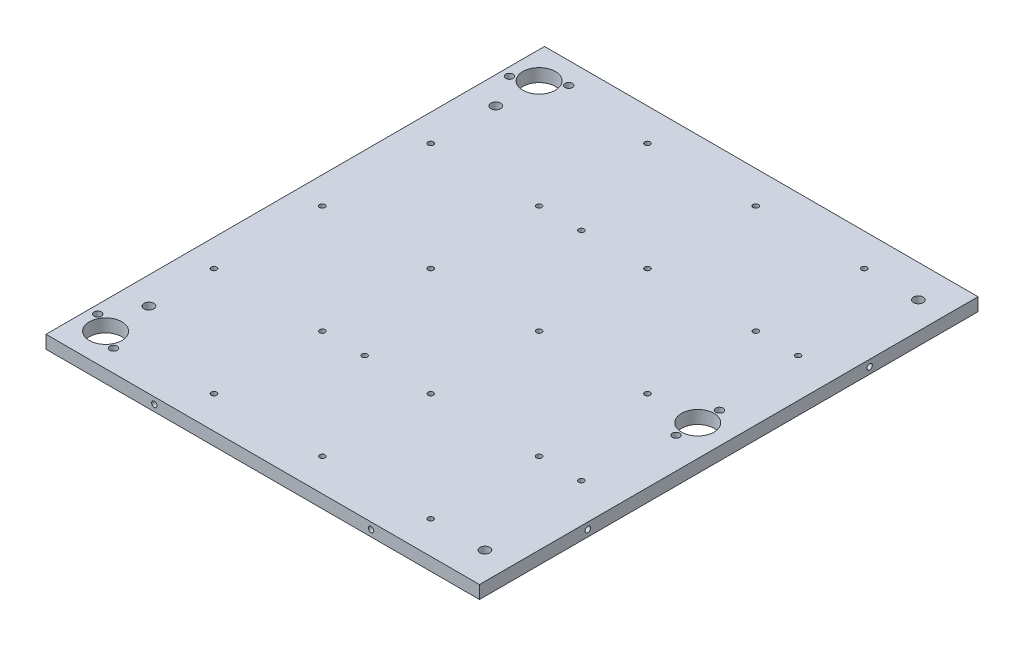
SolidWorks part; units mm, degrees
ref_plane "Ebene vorne" through (0, 0, 0) normal (0, 0, 1) x (1, 0, 0)
ref_plane "Ebene oben" through (0, 0, 0) normal (0, 1, 0) x (1, 0, 0)
ref_plane "Ebene rechts" through (0, 0, 0) normal (1, 0, 0) x (0, 0, -1)
ref_plane "Ebene1" through (0, -162, 0) normal (0, -1, 0) x (1, 0, 0)
sketch "Skizze1" plane through (0, -162, 0) normal (0, -1, 0) x (1, 0, 0)
  line L0 (-2.383, 209.2265) -> (-2.383, -20.7735)
  line L1 (-2.383, -20.7735) -> (197.617, -20.7735)
  line L2 (197.617, -20.7735) -> (197.617, 209.2265)
  line L3 (197.617, 209.2265) -> (-2.383, 209.2265)
extrude "Aufsatz-Linear austragen1" add sketch "Skizze1" against normal blind 6
hole_wizard "Pillar Mounting A" positions "Skizze3" profile "Skizze2" hole size "Ø3.4" standard "Ansi Metrisch"
sketch "Skizze3" plane through (0, -162, 0) normal (0, -1, 0) x (-1, 0, 0)
  point P0 (-1.4567, 0.7735)
  point P1 (-18.7772, 10.7735)
sketch "Skizze2" plane through (1.4567, -162, -0.7735) normal (1, 0, 0) x (0, 0, -1)
  line L0 (0, 0) -> (0, 6)
  line L1 (0, 6) -> (1.7, 6)
  line L2 (1.7, 6) -> (1.7, 0)
  line L5 (1.7, 0) -> (0, 0)
  line L11 (0, -6.35) -> (0, 107.95) construction
  dimension "Bohrerdurchmesser" = 3.4
  dimension "Bohrungstiefe" = 6
hole_wizard "Pillar Grommet" positions "Skizze5" profile "Skizze4" hole size "Ø15.0" standard "Ansi Metrisch"
sketch "Skizze5" plane through (0, -162, 0) normal (0, -1, 0) x (-1, 0, 0)
  point P0 (-10.117, 5.7735)
  point P1 (-10.117, -194.2265)
  point P2 (-183.3221, -94.2265)
sketch "Skizze4" plane through (10.117, -162, -5.7735) normal (1, 0, 0) x (0, 0, -1)
  line L0 (0, 0) -> (0, 6)
  line L1 (0, 6) -> (7.5, 6)
  line L2 (7.5, 6) -> (7.5, 0)
  line L5 (7.5, 0) -> (0, 0)
  line L11 (0, -6.35) -> (0, 107.95) construction
  dimension "Bohrerdurchmesser" = 15
  dimension "Bohrungstiefe" = 6
hole_wizard "Pillar Mounting B" positions "Skizze7" profile "Skizze6" hole size "Ø3.4" standard "Ansi Metrisch"
sketch "Skizze7" plane through (0, -156, 0) normal (0, 1, 0) x (1, 0, 0)
  point P0 (183.3221, -84.2265)
  point P1 (18.7772, -199.2265)
  point P2 (1.4567, -189.2265)
  point P3 (183.3221, -104.2265)
sketch "Skizze6" plane through (183.3221, -156, 84.2265) normal (1, 0, 0) x (0, 0, 1)
  line L0 (0, 0) -> (0, 6)
  line L1 (0, 6) -> (1.7, 6)
  line L2 (1.7, 6) -> (1.7, 0)
  line L5 (1.7, 0) -> (0, 0)
  line L11 (0, -6.35) -> (0, 107.95) construction
  dimension "Bohrerdurchmesser" = 3.4
  dimension "Bohrungstiefe" = 6
hole_wizard "M3 Mounting Grid" positions "Skizze9" profile "Skizze8" tap size "M3x0.5" standard "Ansi Metrisch" end condition through all
sketch "Skizze9" plane through (0, -162, 0) normal (0, -1, 0) x (-1, 0, 0)
  point P0 (-60.117, -94.2265)
  point P1 (-60.117, 5.7735)
  point P2 (-60.117, -44.2265)
  point P3 (-110.117, -44.2265)
  point P4 (-110.117, -194.2265)
  point P5 (-110.117, -94.2265)
  point P6 (-110.117, 5.7735)
  point P7 (-110.117, -144.2265)
  point P8 (-60.117, -144.2265)
  point P9 (-10.117, -144.2265)
  point P10 (-10.117, -44.2265)
  point P11 (-60.117, -194.2265)
  point P12 (-160.117, -94.2265)
  point P13 (-160.117, -44.2265)
  point P14 (-160.117, -194.2265)
  point P15 (-160.117, 5.7735)
  point P16 (-160.117, -144.2265)
  point P17 (-10.117, -94.2265)
sketch "Skizze8" plane through (60.117, -162, 94.2265) normal (1, 0, 0) x (0, 0, -1)
  line L0 (0, 0) -> (0, 6)
  line L1 (0, 6) -> (1.25, 6)
  line L2 (1.25, 6) -> (1.25, 0)
  line L5 (1.25, 0) -> (0, 0)
  line L11 (0, -6.35) -> (0, 107.95) construction
  dimension "Bohrerdurchmesser" = 2.5
  dimension "Bohrungstiefe" = 6
cosmetic thread "Bohrungsgewinde9" parameters "D2"=3
cosmetic thread "Bohrungsgewinde10" parameters "D2"=3
cosmetic thread "Bohrungsgewinde11" parameters "D2"=3
cosmetic thread "Bohrungsgewinde12" parameters "D2"=3
cosmetic thread "Bohrungsgewinde13" parameters "D2"=3
cosmetic thread "Bohrungsgewinde14" parameters "D2"=3
cosmetic thread "Bohrungsgewinde15" parameters "D2"=3
cosmetic thread "Bohrungsgewinde16" parameters "D2"=3
cosmetic thread "Bohrungsgewinde17" parameters "D2"=3
cosmetic thread "Bohrungsgewinde18" parameters "D2"=3
cosmetic thread "Bohrungsgewinde19" parameters "D2"=3
cosmetic thread "Bohrungsgewinde20" parameters "D2"=3
cosmetic thread "Bohrungsgewinde21" parameters "D2"=3
cosmetic thread "Bohrungsgewinde22" parameters "D2"=3
cosmetic thread "Bohrungsgewinde23" parameters "D2"=3
cosmetic thread "Bohrungsgewinde24" parameters "D2"=3
cosmetic thread "Bohrungsgewinde25" parameters "D2"=3
cosmetic thread "Bohrungsgewinde26" parameters "D2"=3
hole_wizard "Pedestal Mounting Hole" positions "Skizze11" profile "Skizze10" countersink size "M4" standard "Ansi Metrisch" end condition through all
sketch "Skizze11" plane through (0, -162, 0) normal (0, -1, 0) x (-1, 0, 0)
  point P0 (-10.117, -174.2265)
  point P1 (-185.117, -194.2265)
  point P2 (-185.117, 5.7735)
  point P3 (-10.117, -14.2265)
sketch "Skizze10" plane through (10.117, -162, 174.2265) normal (1, 0, 0) x (0, 0, -1)
  line L0 (0, 0) -> (0, 6)
  line L1 (0, 6) -> (2.25, 6)
  line L2 (2.25, 6) -> (2.25, 2.23)
  line L3 (2.25, 2.23) -> (4.48, 0)
  line L5 (4.48, 0) -> (0, 0)
  line L6 (-2.25, 2.23) -> (-4.48, 0) construction
  line L11 (0, -6.35) -> (0, 107.95) construction
  dimension "Bohrerdurchmesser" = 4.5
  dimension "Bohrungstiefe" = 6
  dimension "Senkdurchmesser (Oben)" = 8.96
  dimension "Senkwinkel (Oben)" = 90
hole_wizard "Side Cover Mounting Thread A" positions "Skizze13" profile "Skizze12" tap size "M3x0.5" standard "Ansi Metrisch"
sketch "Skizze13" plane through (0, 0, 209.2265) normal (0, 0, 1) x (1, 0, 0)
  point P0 (47.617, -159)
  point P1 (147.617, -159)
sketch "Skizze12" plane through (47.617, -159, 209.2265) normal (1, 0, 0) x (0, -1, 0)
  line L0 (0, 0) -> (0, 9.2511)
  line L1 (0, 9.2511) -> (1.25, 8.5)
  line L2 (1.25, 8.5) -> (1.25, 0)
  line L5 (1.25, 0) -> (0, 0)
  line L10 (0, 9.2511) -> (-1.25, 8.5) construction
  line L11 (0, -6.35) -> (0, 107.95) construction
  dimension "Bohrerdurchmesser" = 2.5
  dimension "Bohrungstiefe" = 8.5
  dimension "Spitzenwinkel" = 118
cosmetic thread "Bohrungsgewinde3" parameters "D1"=6, "D2"=3
cosmetic thread "Bohrungsgewinde4" parameters "D1"=6, "D2"=3
hole_wizard "Side Cover Mounting Thread B" positions "Skizze15" profile "Skizze14" tap size "M3x0.5" standard "Ansi Metrisch"
sketch "Skizze15" plane through (197.617, 0, 0) normal (1, 0, 0) x (0, 0, -1)
  point P0 (-29.2265, -159)
  point P1 (-159.2265, -159)
sketch "Skizze14" plane through (197.617, -159, 29.2265) normal (0, 1, 0) x (0, 0, -1)
  line L0 (0, 0) -> (0, 9.2511)
  line L1 (0, 9.2511) -> (1.25, 8.5)
  line L2 (1.25, 8.5) -> (1.25, 0)
  line L5 (1.25, 0) -> (0, 0)
  line L10 (0, 9.2511) -> (-1.25, 8.5) construction
  line L11 (0, -6.35) -> (0, 107.95) construction
  dimension "Bohrerdurchmesser" = 2.5
  dimension "Bohrungstiefe" = 8.5
  dimension "Spitzenwinkel" = 118
cosmetic thread "Bohrungsgewinde5" parameters "D1"=6, "D2"=3
cosmetic thread "Bohrungsgewinde6" parameters "D1"=6, "D2"=3
hole_wizard "Side Cover Mounting Thread  C" positions "Skizze17" profile "Skizze16" tap size "M3x0.5" standard "Ansi Metrisch"
sketch "Skizze17" plane through (0, 0, -20.7735) normal (0, 0, -1) x (-1, 0, 0)
  point P0 (-47.617, -159)
  point P1 (-147.617, -159)
sketch "Skizze16" plane through (47.617, -159, -20.7735) normal (1, 0, 0) x (0, 1, 0)
  line L0 (0, 0) -> (0, 9.2511)
  line L1 (0, 9.2511) -> (1.25, 8.5)
  line L2 (1.25, 8.5) -> (1.25, 0)
  line L5 (1.25, 0) -> (0, 0)
  line L10 (0, 9.2511) -> (-1.25, 8.5) construction
  line L11 (0, -6.35) -> (0, 107.95) construction
  dimension "Bohrerdurchmesser" = 2.5
  dimension "Bohrungstiefe" = 8.5
  dimension "Spitzenwinkel" = 118
cosmetic thread "Bohrungsgewinde1" parameters "D1"=6, "D2"=3
cosmetic thread "Bohrungsgewinde2" parameters "D1"=6, "D2"=3
hole_wizard "Side Cover Mounting Thread  D" positions "Skizze19" profile "Skizze18" tap size "M3x0.5" standard "Ansi Metrisch"
sketch "Skizze19" plane through (-2.383, 0, 0) normal (-1, 0, 0) x (0, 0, 1)
  point P0 (29.2265, -159)
  point P1 (159.2265, -159)
sketch "Skizze18" plane through (-2.383, -159, 29.2265) normal (0, 1, 0) x (0, 0, 1)
  line L0 (0, 0) -> (0, 9.2511)
  line L1 (0, 9.2511) -> (1.25, 8.5)
  line L2 (1.25, 8.5) -> (1.25, 0)
  line L5 (1.25, 0) -> (0, 0)
  line L10 (0, 9.2511) -> (-1.25, 8.5) construction
  line L11 (0, -6.35) -> (0, 107.95) construction
  dimension "Bohrerdurchmesser" = 2.5
  dimension "Bohrungstiefe" = 8.5
  dimension "Spitzenwinkel" = 118
cosmetic thread "Bohrungsgewinde7" parameters "D1"=6, "D2"=3
cosmetic thread "Bohrungsgewinde8" parameters "D1"=6, "D2"=3
hole_wizard "Mainboard Mounting" positions "Skizze23" profile "Skizze22" tap size "M3x0.5" standard "Ansi Metrisch" end condition through all
sketch "Skizze23" plane through (0, -162, 0) normal (0, -1, 0) x (-1, 0, 0)
  line L0 (-197.617, 20.7735) -> (-197.617, -209.2265) construction
  line L1 (-197.617, -209.2265) -> (2.383, -209.2265) construction
  point P0 (-179.617, -144.2265)
  dimension "D1" = 18
  dimension "D2" = 65
sketch "Skizze22" plane through (179.617, -162, 144.2265) normal (1, 0, 0) x (0, 0, -1)
  line L0 (0, 0) -> (0, 6)
  line L1 (0, 6) -> (1.25, 6)
  line L2 (1.25, 6) -> (1.25, 0)
  line L5 (1.25, 0) -> (0, 0)
  line L11 (0, -6.35) -> (0, 107.95) construction
  dimension "Bohrerdurchmesser" = 2.5
  dimension "Bohrungstiefe" = 6
cosmetic thread "Bohrungsgewinde27" parameters "D2"=3
pattern_linear "Lineares Muster1" count 2 spacing 100 along (-1, 0, 0) count 2 spacing 100 along (0, 0, -1) of "Mainboard Mounting"
